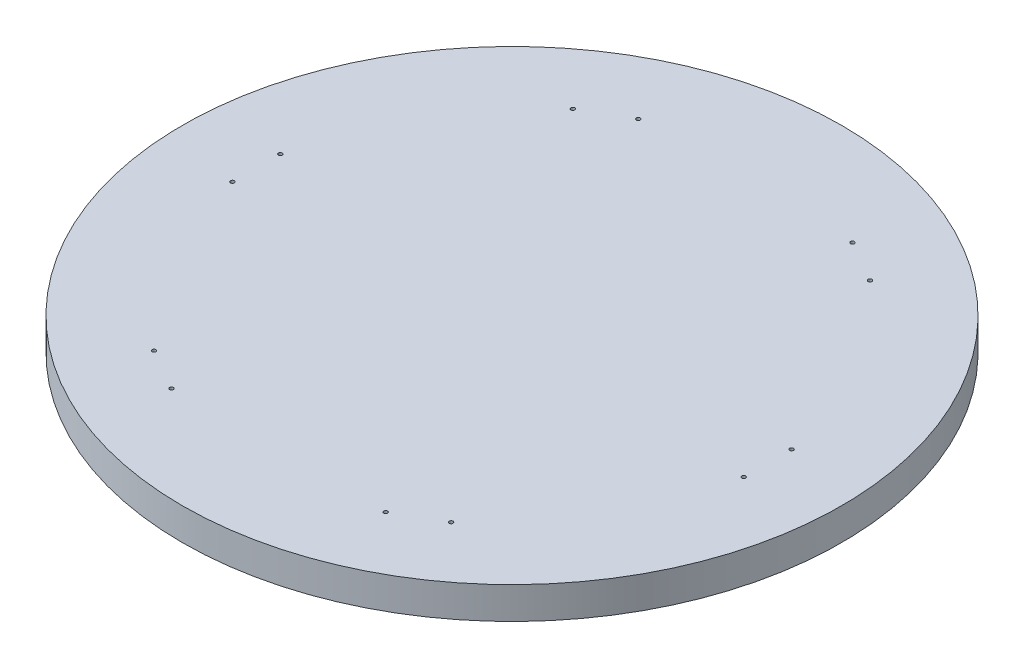
SolidWorks part; units mm, degrees
ref_plane "Front Plane" through (0, 0, 0) normal (0, 0, 1) x (1, 0, 0)
ref_plane "Top Plane" through (0, 0, 0) normal (0, 1, 0) x (1, 0, 0)
ref_plane "Right Plane" through (0, 0, 0) normal (1, 0, 0) x (0, 0, -1)
sketch "Sketch1" plane through (0, 0, 0) normal (0, 1, 0) x (1, 0, 0)
  circle A0 centre (0, 0) radius 261.9375
extrude "Boss-Extrude1" add sketch "Sketch1" along normal blind 25.4
sketch "Sketch6" plane through (0, 0, 0) normal (0, -1, 0) x (1, 0, 0)
  line L0 (203.2, 19.05) -> (203.2, -19.05) construction
  line L1 (215.9, 19.05) -> (215.9, -19.05)
  line L2 (190.5, 19.05) -> (190.5, -19.05)
  line L3 (203.2, -16.5451) -> (201.0307, -17.7976) construction
  line L4 (201.0307, -17.7976) -> (201.0307, -20.3024) construction
  line L5 (201.0307, -20.3024) -> (203.2, -21.5549) construction
  line L6 (203.2, -21.5549) -> (205.3693, -20.3024) construction
  line L7 (205.3693, -20.3024) -> (205.3693, -17.7976) construction
  line L8 (205.3693, -17.7976) -> (203.2, -16.5451) construction
  line L9 (203.2, 22.1294) -> (201.0307, 20.8769) construction
  line L10 (201.0307, 20.8769) -> (201.0307, 18.372) construction
  line L11 (201.0307, 18.372) -> (203.2, 17.1196) construction
  line L12 (203.2, 17.1196) -> (205.3693, 18.372) construction
  line L13 (205.3693, 18.372) -> (205.3693, 20.8769) construction
  line L14 (205.3693, 20.8769) -> (203.2, 22.1294) construction
  line L15 (0, 0) -> (203.2, 0) construction
  line L16 (87.2715, -184.2489) -> (85.1022, -182.9965) construction
  line L17 (85.1022, -182.9965) -> (82.9329, -184.2489) construction
  line L18 (82.9329, -184.2489) -> (82.9329, -186.7538) construction
  line L19 (82.9329, -186.7538) -> (85.1022, -188.0063) construction
  line L20 (85.1022, -188.0063) -> (87.2715, -186.7538) construction
  line L21 (87.2715, -186.7538) -> (87.2715, -184.2489) construction
  line L22 (120.7646, -164.9117) -> (118.5953, -163.6592) construction
  line L23 (118.5953, -163.6592) -> (116.426, -164.9117) construction
  line L24 (116.426, -164.9117) -> (116.426, -167.4166) construction
  line L25 (116.426, -167.4166) -> (118.5953, -168.669) construction
  line L26 (118.5953, -168.669) -> (120.7646, -167.4166) construction
  line L27 (120.7646, -167.4166) -> (120.7646, -164.9117) construction
  line L28 (0, 0) -> (101.6, -175.9764) construction
  line L29 (118.0978, -166.4514) -> (85.1022, -185.5014) construction
  line L30 (124.4478, -177.4499) -> (91.4522, -196.4999)
  line L31 (111.7478, -155.4528) -> (78.7522, -174.5028)
  line L32 (-115.9285, -167.7038) -> (-115.9285, -165.1989) construction
  line L33 (-115.9285, -165.1989) -> (-118.0978, -163.9465) construction
  line L34 (-118.0978, -163.9465) -> (-120.2671, -165.1989) construction
  line L35 (-120.2671, -165.1989) -> (-120.2671, -167.7038) construction
  line L36 (-120.2671, -167.7038) -> (-118.0978, -168.9563) construction
  line L37 (-118.0978, -168.9563) -> (-115.9285, -167.7038) construction
  line L38 (-82.4354, -187.0411) -> (-82.4354, -184.5362) construction
  line L39 (-82.4354, -184.5362) -> (-84.6047, -183.2837) construction
  line L40 (-84.6047, -183.2837) -> (-86.774, -184.5362) construction
  line L41 (-86.774, -184.5362) -> (-86.774, -187.0411) construction
  line L42 (-86.774, -187.0411) -> (-84.6047, -188.2935) construction
  line L43 (-84.6047, -188.2935) -> (-82.4354, -187.0411) construction
  line L44 (0, 0) -> (-101.6, -175.9764) construction
  line L45 (-85.1022, -185.5014) -> (-118.0978, -166.4514) construction
  line L46 (-91.4522, -196.4999) -> (-124.4478, -177.4499)
  line L47 (-78.7522, -174.5028) -> (-111.7478, -155.4528)
  line L48 (-203.2, 16.5451) -> (-201.0307, 17.7976) construction
  line L49 (-201.0307, 17.7976) -> (-201.0307, 20.3024) construction
  line L50 (-201.0307, 20.3024) -> (-203.2, 21.5549) construction
  line L51 (-203.2, 21.5549) -> (-205.3693, 20.3024) construction
  line L52 (-205.3693, 20.3024) -> (-205.3693, 17.7976) construction
  line L53 (-205.3693, 17.7976) -> (-203.2, 16.5451) construction
  line L54 (-203.2, -22.1294) -> (-201.0307, -20.8769) construction
  line L55 (-201.0307, -20.8769) -> (-201.0307, -18.372) construction
  line L56 (-201.0307, -18.372) -> (-203.2, -17.1196) construction
  line L57 (-203.2, -17.1196) -> (-205.3693, -18.372) construction
  line L58 (-205.3693, -18.372) -> (-205.3693, -20.8769) construction
  line L59 (-205.3693, -20.8769) -> (-203.2, -22.1294) construction
  line L60 (0, 0) -> (-203.2, 0) construction
  line L61 (-203.2, -19.05) -> (-203.2, 19.05) construction
  line L62 (-215.9, -19.05) -> (-215.9, 19.05)
  line L63 (-190.5, -19.05) -> (-190.5, 19.05)
  line L64 (-87.2715, 184.2489) -> (-85.1022, 182.9965) construction
  line L65 (-85.1022, 182.9965) -> (-82.9329, 184.2489) construction
  line L66 (-82.9329, 184.2489) -> (-82.9329, 186.7538) construction
  line L67 (-82.9329, 186.7538) -> (-85.1022, 188.0063) construction
  line L68 (-85.1022, 188.0063) -> (-87.2715, 186.7538) construction
  line L69 (-87.2715, 186.7538) -> (-87.2715, 184.2489) construction
  line L70 (-120.7646, 164.9117) -> (-118.5953, 163.6592) construction
  line L71 (-118.5953, 163.6592) -> (-116.426, 164.9117) construction
  line L72 (-116.426, 164.9117) -> (-116.426, 167.4166) construction
  line L73 (-116.426, 167.4166) -> (-118.5953, 168.669) construction
  line L74 (-118.5953, 168.669) -> (-120.7646, 167.4166) construction
  line L75 (-120.7646, 167.4166) -> (-120.7646, 164.9117) construction
  line L76 (0, 0) -> (-101.6, 175.9764) construction
  line L77 (-118.0978, 166.4514) -> (-85.1022, 185.5014) construction
  line L78 (-124.4478, 177.4499) -> (-91.4522, 196.4999)
  line L79 (-111.7478, 155.4528) -> (-78.7522, 174.5028)
  line L80 (115.9285, 167.7038) -> (115.9285, 165.1989) construction
  line L81 (115.9285, 165.1989) -> (118.0978, 163.9465) construction
  line L82 (118.0978, 163.9465) -> (120.2671, 165.1989) construction
  line L83 (120.2671, 165.1989) -> (120.2671, 167.7038) construction
  line L84 (120.2671, 167.7038) -> (118.0978, 168.9563) construction
  line L85 (118.0978, 168.9563) -> (115.9285, 167.7038) construction
  line L86 (82.4354, 187.0411) -> (82.4354, 184.5362) construction
  line L87 (82.4354, 184.5362) -> (84.6047, 183.2837) construction
  line L88 (84.6047, 183.2837) -> (86.774, 184.5362) construction
  line L89 (86.774, 184.5362) -> (86.774, 187.0411) construction
  line L90 (86.774, 187.0411) -> (84.6047, 188.2935) construction
  line L91 (84.6047, 188.2935) -> (82.4354, 187.0411) construction
  line L92 (0, 0) -> (101.6, 175.9764) construction
  line L93 (85.1022, 185.5014) -> (118.0978, 166.4514) construction
  line L94 (91.4522, 196.4999) -> (124.4478, 177.4499)
  line L95 (78.7522, 174.5028) -> (111.7478, 155.4528)
  arc A0 (215.9, 19.05) -> (190.5, 19.05) centre (203.2, 19.05) ccw
  arc A1 (190.5, -19.05) -> (215.9, -19.05) centre (203.2, -19.05) ccw
  circle A2 centre (203.2, -19.05) radius 2.1693 construction
  circle A3 centre (203.2, 19.6245) radius 2.1693 construction
  circle A4 centre (203.2, -19.05) radius 1.524 construction
  circle A5 centre (203.2, 19.6245) radius 1.524 construction
  circle A6 centre (85.1022, -185.5014) radius 2.1693 construction
  circle A7 centre (118.5953, -166.1641) radius 2.1693 construction
  circle A8 centre (85.1022, -185.5014) radius 1.524 construction
  circle A9 centre (118.5953, -166.1641) radius 1.524 construction
  arc A10 (124.4478, -177.4499) -> (111.7478, -155.4528) centre (118.0978, -166.4514) ccw
  arc A11 (78.7522, -174.5028) -> (91.4522, -196.4999) centre (85.1022, -185.5014) ccw
  circle A12 centre (-118.0978, -166.4514) radius 2.1693 construction
  circle A13 centre (-84.6047, -185.7886) radius 2.1693 construction
  circle A14 centre (-118.0978, -166.4514) radius 1.524 construction
  circle A15 centre (-84.6047, -185.7886) radius 1.524 construction
  arc A16 (-91.4522, -196.4999) -> (-78.7522, -174.5028) centre (-85.1022, -185.5014) ccw
  arc A17 (-111.7478, -155.4528) -> (-124.4478, -177.4499) centre (-118.0978, -166.4514) ccw
  circle A18 centre (-203.2, 19.05) radius 2.1693 construction
  circle A19 centre (-203.2, -19.6245) radius 2.1693 construction
  circle A20 centre (-203.2, 19.05) radius 1.524 construction
  circle A21 centre (-203.2, -19.6245) radius 1.524 construction
  arc A22 (-215.9, -19.05) -> (-190.5, -19.05) centre (-203.2, -19.05) ccw
  arc A23 (-190.5, 19.05) -> (-215.9, 19.05) centre (-203.2, 19.05) ccw
  circle A24 centre (-85.1022, 185.5014) radius 2.1693 construction
  circle A25 centre (-118.5953, 166.1641) radius 2.1693 construction
  circle A26 centre (-85.1022, 185.5014) radius 1.524 construction
  circle A27 centre (-118.5953, 166.1641) radius 1.524 construction
  arc A28 (-124.4478, 177.4499) -> (-111.7478, 155.4528) centre (-118.0978, 166.4514) ccw
  arc A29 (-78.7522, 174.5028) -> (-91.4522, 196.4999) centre (-85.1022, 185.5014) ccw
  circle A30 centre (118.0978, 166.4514) radius 2.1693 construction
  circle A31 centre (84.6047, 185.7886) radius 2.1693 construction
  circle A32 centre (118.0978, 166.4514) radius 1.524 construction
  circle A33 centre (84.6047, 185.7886) radius 1.524 construction
  arc A34 (91.4522, 196.4999) -> (78.7522, 174.5028) centre (85.1022, 185.5014) ccw
  arc A35 (111.7478, 155.4528) -> (124.4478, 177.4499) centre (118.0978, 166.4514) ccw
  point P2 (203.2, 0)
  point P32 (101.6, -175.9764)
  point P58 (-101.6, -175.9764)
  point P84 (-203.2, 0)
  point P110 (-101.6, 175.9764)
  point P136 (101.6, 175.9764)
  point P160 (0, 0)
  dimension "D1" = 6
extrude "Cut-Extrude4" cut sketch "Sketch6" against normal blind 12.7
sketch "Sketch9" plane through (0, 0, 0) normal (0, -1, 0) x (1, 0, 0)
  circle A0 centre (0, 0) radius 25.4
extrude "Boss-Extrude2" add sketch "Sketch9" along normal blind 10.16 and the other way through all
sketch "Sketch10" plane through (0, -10.16, 0) normal (0, -1, 0) x (1, 0, 0)
  line L0 (0, -2.032) -> (0, 1.524) construction
  line L1 (-1.344, 1.524) -> (1.344, 1.524)
  line L2 (-2.032, 0) -> (-2.032, 1.524)
  line L3 (-2.032, 1.524) -> (-1.344, 1.524)
  line L4 (2.032, 0) -> (2.032, 1.524)
  line L5 (2.032, 1.524) -> (1.344, 1.524)
  arc A0 (-2.032, 0) -> (2.032, 0) centre (0, 0) ccw
extrude "Cut-Extrude7" cut sketch "Sketch10" against normal blind 19.05
sketch "Sketch11" plane through (0, 0, 0) normal (0, -1, 0) x (1, 0, 0)
  line L0 (0, 0) -> (-11.1642, -177.4492) construction
  line L1 (0, 0) -> (0, -291.8902) construction
  line L2 (0, 0) -> (11.1642, -177.4492) construction
  line L3 (-33.3164, -174.6507) -> (-22.2403, -176.0499) construction
  line L4 (-11.1642, -177.4492) -> (0, -177.4492) construction
  line L5 (0, -177.4492) -> (11.1642, -177.4492) construction
  line L6 (-22.2403, -176.0499) -> (-11.1642, -177.4492) construction
  line L7 (-54.9432, -169.0978) -> (-44.1298, -171.8743) construction
  line L8 (-44.1298, -171.8743) -> (-33.3164, -174.6507) construction
  line L9 (-75.7036, -160.8782) -> (-65.3234, -164.988) construction
  line L10 (-65.3234, -164.988) -> (-54.9432, -169.0978) construction
  line L11 (-95.27, -150.1215) -> (-85.4868, -155.4999) construction
  line L12 (-85.4868, -155.4999) -> (-75.7036, -160.8782) construction
  line L13 (-113.334, -136.9973) -> (-104.302, -143.5594) construction
  line L14 (-104.302, -143.5594) -> (-95.27, -150.1215) construction
  line L15 (-129.6106, -121.7125) -> (-121.4723, -129.3549) construction
  line L16 (-121.4723, -129.3549) -> (-113.334, -136.9973) construction
  line L17 (-143.8432, -104.5082) -> (-136.7269, -113.1103) construction
  line L18 (-136.7269, -113.1103) -> (-129.6106, -121.7125) construction
  line L19 (-155.8073, -85.6558) -> (-149.8253, -95.082) construction
  line L20 (-149.8253, -95.082) -> (-143.8432, -104.5082) construction
  line L21 (-165.3143, -65.4525) -> (-160.5608, -75.5542) construction
  line L22 (-160.5608, -75.5542) -> (-155.8073, -85.6558) construction
  line L23 (-172.2141, -44.2171) -> (-168.7642, -54.8348) construction
  line L24 (-168.7642, -54.8348) -> (-165.3143, -65.4525) construction
  line L25 (-176.398, -22.2842) -> (-174.306, -33.2507) construction
  line L26 (-174.306, -33.2507) -> (-172.2141, -44.2171) construction
  line L27 (-177.8, 0) -> (-177.099, -11.1421) construction
  line L28 (-177.099, -11.1421) -> (-176.398, -22.2842) construction
  line L29 (-176.398, 22.2842) -> (-177.099, 11.1421) construction
  line L30 (-177.099, 11.1421) -> (-177.8, 0) construction
  line L31 (-172.2141, 44.2171) -> (-174.306, 33.2507) construction
  line L32 (-174.306, 33.2507) -> (-176.398, 22.2842) construction
  line L33 (-165.3143, 65.4525) -> (-168.7642, 54.8348) construction
  line L34 (-168.7642, 54.8348) -> (-172.2141, 44.2171) construction
  line L35 (-155.8073, 85.6558) -> (-160.5608, 75.5542) construction
  line L36 (-160.5608, 75.5542) -> (-165.3143, 65.4525) construction
  line L37 (-143.8432, 104.5082) -> (-149.8253, 95.082) construction
  line L38 (-149.8253, 95.082) -> (-155.8073, 85.6558) construction
  line L39 (-129.6106, 121.7125) -> (-136.7269, 113.1103) construction
  line L40 (-136.7269, 113.1103) -> (-143.8432, 104.5082) construction
  line L41 (-113.334, 136.9973) -> (-121.4723, 129.3549) construction
  line L42 (-121.4723, 129.3549) -> (-129.6106, 121.7125) construction
  line L43 (-95.27, 150.1215) -> (-104.302, 143.5594) construction
  line L44 (-104.302, 143.5594) -> (-113.334, 136.9973) construction
  line L45 (-75.7036, 160.8782) -> (-85.4868, 155.4999) construction
  line L46 (-85.4868, 155.4999) -> (-95.27, 150.1215) construction
  line L47 (-54.9432, 169.0978) -> (-65.3234, 164.988) construction
  line L48 (-65.3234, 164.988) -> (-75.7036, 160.8782) construction
  line L49 (-33.3164, 174.6507) -> (-44.1298, 171.8743) construction
  line L50 (-44.1298, 171.8743) -> (-54.9432, 169.0978) construction
  line L51 (-11.1642, 177.4492) -> (-22.2403, 176.0499) construction
  line L52 (-22.2403, 176.0499) -> (-33.3164, 174.6507) construction
  line L53 (11.1642, 177.4492) -> (0, 177.4492) construction
  line L54 (0, 177.4492) -> (-11.1642, 177.4492) construction
  line L55 (33.3164, 174.6507) -> (22.2403, 176.0499) construction
  line L56 (22.2403, 176.0499) -> (11.1642, 177.4492) construction
  line L57 (54.9432, 169.0978) -> (44.1298, 171.8743) construction
  line L58 (44.1298, 171.8743) -> (33.3164, 174.6507) construction
  line L59 (75.7036, 160.8782) -> (65.3234, 164.988) construction
  line L60 (65.3234, 164.988) -> (54.9432, 169.0978) construction
  line L61 (95.27, 150.1215) -> (85.4868, 155.4999) construction
  line L62 (85.4868, 155.4999) -> (75.7036, 160.8782) construction
  line L63 (113.334, 136.9973) -> (104.302, 143.5594) construction
  line L64 (104.302, 143.5594) -> (95.27, 150.1215) construction
  line L65 (129.6106, 121.7125) -> (121.4723, 129.3549) construction
  line L66 (121.4723, 129.3549) -> (113.334, 136.9973) construction
  line L67 (143.8432, 104.5082) -> (136.7269, 113.1103) construction
  line L68 (136.7269, 113.1103) -> (129.6106, 121.7125) construction
  line L69 (155.8073, 85.6558) -> (149.8253, 95.082) construction
  line L70 (149.8253, 95.082) -> (143.8432, 104.5082) construction
  line L71 (165.3143, 65.4525) -> (160.5608, 75.5542) construction
  line L72 (160.5608, 75.5542) -> (155.8073, 85.6558) construction
  line L73 (172.2141, 44.2171) -> (168.7642, 54.8348) construction
  line L74 (168.7642, 54.8348) -> (165.3143, 65.4525) construction
  line L75 (176.398, 22.2842) -> (174.306, 33.2507) construction
  line L76 (174.306, 33.2507) -> (172.2141, 44.2171) construction
  line L77 (177.8, 0) -> (177.099, 11.1421) construction
  line L78 (177.099, 11.1421) -> (176.398, 22.2842) construction
  line L79 (176.398, -22.2842) -> (177.099, -11.1421) construction
  line L80 (177.099, -11.1421) -> (177.8, 0) construction
  line L81 (172.2141, -44.2171) -> (174.306, -33.2507) construction
  line L82 (174.306, -33.2507) -> (176.398, -22.2842) construction
  line L83 (165.3143, -65.4525) -> (168.7642, -54.8348) construction
  line L84 (168.7642, -54.8348) -> (172.2141, -44.2171) construction
  line L85 (155.8073, -85.6558) -> (160.5608, -75.5542) construction
  line L86 (160.5608, -75.5542) -> (165.3143, -65.4525) construction
  line L87 (143.8432, -104.5082) -> (149.8253, -95.082) construction
  line L88 (149.8253, -95.082) -> (155.8073, -85.6558) construction
  line L89 (129.6106, -121.7125) -> (136.7269, -113.1103) construction
  line L90 (136.7269, -113.1103) -> (143.8432, -104.5082) construction
  line L91 (113.334, -136.9973) -> (121.4723, -129.3549) construction
  line L92 (121.4723, -129.3549) -> (129.6106, -121.7125) construction
  line L93 (95.27, -150.1215) -> (104.302, -143.5594) construction
  line L94 (104.302, -143.5594) -> (113.334, -136.9973) construction
  line L95 (75.7036, -160.8782) -> (85.4868, -155.4999) construction
  line L96 (85.4868, -155.4999) -> (95.27, -150.1215) construction
  line L97 (54.9432, -169.0978) -> (65.3234, -164.988) construction
  line L98 (65.3234, -164.988) -> (75.7036, -160.8782) construction
  line L99 (33.3164, -174.6507) -> (44.1298, -171.8743) construction
  line L100 (44.1298, -171.8743) -> (54.9432, -169.0978) construction
  line L101 (11.1642, -177.4492) -> (22.2403, -176.0499) construction
  line L102 (22.2403, -176.0499) -> (33.3164, -174.6507) construction
  circle A0 centre (0, 0) radius 177.8 construction
  arc A1 (0, -177.4492) -> (-11.1201, -176.7495) centre (-5.5821, -177.4492) ccw
  arc A2 (0, -177.4492) -> (11.1201, -176.7495) centre (5.5821, -177.4492) ccw
  arc A3 (-22.2403, -176.0499) -> (-33.185, -173.9621) centre (-27.7783, -175.3503) ccw
  arc A4 (-22.2403, -176.0499) -> (-11.1201, -176.7495) centre (-16.7022, -176.7495) ccw
  arc A5 (-44.1298, -171.8743) -> (-54.7266, -168.4312) centre (-49.5365, -170.4861) ccw
  arc A6 (-44.1298, -171.8743) -> (-33.185, -173.9621) centre (-38.7231, -173.2625) ccw
  arc A7 (-65.3234, -164.988) -> (-75.4051, -160.244) centre (-70.5135, -162.9331) ccw
  arc A8 (-65.3234, -164.988) -> (-54.7266, -168.4312) centre (-60.1333, -167.0429) ccw
  arc A9 (-85.4868, -155.4999) -> (-94.8944, -149.5296) centre (-90.3784, -152.8107) ccw
  arc A10 (-85.4868, -155.4999) -> (-75.4051, -160.244) centre (-80.5952, -158.1891) ccw
  arc A11 (-104.302, -143.5594) -> (-112.8871, -136.4571) centre (-108.818, -140.2783) ccw
  arc A12 (-104.302, -143.5594) -> (-94.8944, -149.5296) centre (-99.786, -146.8404) ccw
  arc A13 (-121.4723, -129.3549) -> (-129.0996, -121.2326) centre (-125.5415, -125.5337) ccw
  arc A14 (-121.4723, -129.3549) -> (-112.8871, -136.4571) centre (-117.4031, -133.1761) ccw
  arc A15 (-136.7269, -113.1103) -> (-143.2761, -104.0962) centre (-140.2851, -108.8093) ccw
  arc A16 (-136.7269, -113.1103) -> (-129.0996, -121.2326) centre (-133.1688, -117.4114) ccw
  arc A17 (-149.8253, -95.082) -> (-155.193, -85.3181) centre (-152.8163, -90.3689) ccw
  arc A18 (-149.8253, -95.082) -> (-143.2761, -104.0962) centre (-146.8342, -99.7951) ccw
  arc A19 (-160.5608, -75.5542) -> (-164.6625, -65.1945) centre (-162.9375, -70.5034) ccw
  arc A20 (-160.5608, -75.5542) -> (-155.193, -85.3181) centre (-158.1841, -80.605) ccw
  arc A21 (-168.7642, -54.8348) -> (-171.5351, -44.0427) centre (-170.4891, -49.5259) ccw
  arc A22 (-168.7642, -54.8348) -> (-164.6625, -65.1945) centre (-167.0392, -60.1437) ccw
  arc A23 (-174.306, -33.2507) -> (-175.7025, -22.1964) centre (-175.352, -27.7675) ccw
  arc A24 (-174.306, -33.2507) -> (-171.5351, -44.0427) centre (-173.2601, -38.7339) ccw
  arc A25 (-177.099, -11.1421) -> (-177.099, 0) centre (-177.4495, -5.5711) ccw
  arc A26 (-177.099, -11.1421) -> (-175.7025, -22.1964) centre (-176.7485, -16.7132) ccw
  arc A27 (-177.099, 11.1421) -> (-175.7025, 22.1964) centre (-176.7485, 16.7132) ccw
  arc A28 (-177.099, 11.1421) -> (-177.099, 0) centre (-177.4495, 5.5711) ccw
  arc A29 (-174.306, 33.2507) -> (-171.5351, 44.0427) centre (-173.2601, 38.7339) ccw
  arc A30 (-174.306, 33.2507) -> (-175.7025, 22.1964) centre (-175.352, 27.7675) ccw
  arc A31 (-168.7642, 54.8348) -> (-164.6625, 65.1945) centre (-167.0392, 60.1437) ccw
  arc A32 (-168.7642, 54.8348) -> (-171.5351, 44.0427) centre (-170.4891, 49.5259) ccw
  arc A33 (-160.5608, 75.5542) -> (-155.193, 85.3181) centre (-158.1841, 80.605) ccw
  arc A34 (-160.5608, 75.5542) -> (-164.6625, 65.1945) centre (-162.9375, 70.5034) ccw
  arc A35 (-149.8253, 95.082) -> (-143.2761, 104.0962) centre (-146.8342, 99.7951) ccw
  arc A36 (-149.8253, 95.082) -> (-155.193, 85.3181) centre (-152.8163, 90.3689) ccw
  arc A37 (-136.7269, 113.1103) -> (-129.0996, 121.2326) centre (-133.1688, 117.4114) ccw
  arc A38 (-136.7269, 113.1103) -> (-143.2761, 104.0962) centre (-140.2851, 108.8093) ccw
  arc A39 (-121.4723, 129.3549) -> (-112.8871, 136.4571) centre (-117.4031, 133.1761) ccw
  arc A40 (-121.4723, 129.3549) -> (-129.0996, 121.2326) centre (-125.5415, 125.5337) ccw
  arc A41 (-104.302, 143.5594) -> (-94.8944, 149.5296) centre (-99.786, 146.8404) ccw
  arc A42 (-104.302, 143.5594) -> (-112.8871, 136.4571) centre (-108.818, 140.2783) ccw
  arc A43 (-85.4868, 155.4999) -> (-75.4051, 160.244) centre (-80.5952, 158.1891) ccw
  arc A44 (-85.4868, 155.4999) -> (-94.8944, 149.5296) centre (-90.3784, 152.8107) ccw
  arc A45 (-65.3234, 164.988) -> (-54.7266, 168.4312) centre (-60.1333, 167.0429) ccw
  arc A46 (-65.3234, 164.988) -> (-75.4051, 160.244) centre (-70.5135, 162.9331) ccw
  arc A47 (-44.1298, 171.8743) -> (-33.185, 173.9621) centre (-38.7231, 173.2625) ccw
  arc A48 (-44.1298, 171.8743) -> (-54.7266, 168.4312) centre (-49.5365, 170.4861) ccw
  arc A49 (-22.2403, 176.0499) -> (-11.1201, 176.7495) centre (-16.7022, 176.7495) ccw
  arc A50 (-22.2403, 176.0499) -> (-33.185, 173.9621) centre (-27.7783, 175.3503) ccw
  arc A51 (0, 177.4492) -> (11.1201, 176.7495) centre (5.5821, 177.4492) ccw
  arc A52 (0, 177.4492) -> (-11.1201, 176.7495) centre (-5.5821, 177.4492) ccw
  arc A53 (22.2403, 176.0499) -> (33.185, 173.9621) centre (27.7783, 175.3503) ccw
  arc A54 (22.2403, 176.0499) -> (11.1201, 176.7495) centre (16.7022, 176.7495) ccw
  arc A55 (44.1298, 171.8743) -> (54.7266, 168.4312) centre (49.5365, 170.4861) ccw
  arc A56 (44.1298, 171.8743) -> (33.185, 173.9621) centre (38.7231, 173.2625) ccw
  arc A57 (65.3234, 164.988) -> (75.4051, 160.244) centre (70.5135, 162.9331) ccw
  arc A58 (65.3234, 164.988) -> (54.7266, 168.4312) centre (60.1333, 167.0429) ccw
  arc A59 (85.4868, 155.4999) -> (94.8944, 149.5296) centre (90.3784, 152.8107) ccw
  arc A60 (85.4868, 155.4999) -> (75.4051, 160.244) centre (80.5952, 158.1891) ccw
  arc A61 (104.302, 143.5594) -> (112.8871, 136.4571) centre (108.818, 140.2783) ccw
  arc A62 (104.302, 143.5594) -> (94.8944, 149.5296) centre (99.786, 146.8404) ccw
  arc A63 (121.4723, 129.3549) -> (129.0996, 121.2326) centre (125.5415, 125.5337) ccw
  arc A64 (121.4723, 129.3549) -> (112.8871, 136.4571) centre (117.4031, 133.1761) ccw
  arc A65 (136.7269, 113.1103) -> (143.2761, 104.0962) centre (140.2851, 108.8093) ccw
  arc A66 (136.7269, 113.1103) -> (129.0996, 121.2326) centre (133.1688, 117.4114) ccw
  arc A67 (149.8253, 95.082) -> (155.193, 85.3181) centre (152.8163, 90.3689) ccw
  arc A68 (149.8253, 95.082) -> (143.2761, 104.0962) centre (146.8342, 99.7951) ccw
  arc A69 (160.5608, 75.5542) -> (164.6625, 65.1945) centre (162.9375, 70.5034) ccw
  arc A70 (160.5608, 75.5542) -> (155.193, 85.3181) centre (158.1841, 80.605) ccw
  arc A71 (168.7642, 54.8348) -> (171.5351, 44.0427) centre (170.4891, 49.5259) ccw
  arc A72 (168.7642, 54.8348) -> (164.6625, 65.1945) centre (167.0392, 60.1437) ccw
  arc A73 (174.306, 33.2507) -> (175.7025, 22.1964) centre (175.352, 27.7675) ccw
  arc A74 (174.306, 33.2507) -> (171.5351, 44.0427) centre (173.2601, 38.7339) ccw
  arc A75 (177.099, 11.1421) -> (177.099, 0) centre (177.4495, 5.5711) ccw
  arc A76 (177.099, 11.1421) -> (175.7025, 22.1964) centre (176.7485, 16.7132) ccw
  arc A77 (177.099, -11.1421) -> (175.7025, -22.1964) centre (176.7485, -16.7132) ccw
  arc A78 (177.099, -11.1421) -> (177.099, 0) centre (177.4495, -5.5711) ccw
  arc A79 (174.306, -33.2507) -> (171.5351, -44.0427) centre (173.2601, -38.7339) ccw
  arc A80 (174.306, -33.2507) -> (175.7025, -22.1964) centre (175.352, -27.7675) ccw
  arc A81 (168.7642, -54.8348) -> (164.6625, -65.1945) centre (167.0392, -60.1437) ccw
  arc A82 (168.7642, -54.8348) -> (171.5351, -44.0427) centre (170.4891, -49.5259) ccw
  arc A83 (160.5608, -75.5542) -> (155.193, -85.3181) centre (158.1841, -80.605) ccw
  arc A84 (160.5608, -75.5542) -> (164.6625, -65.1945) centre (162.9375, -70.5034) ccw
  arc A85 (149.8253, -95.082) -> (143.2761, -104.0962) centre (146.8342, -99.7951) ccw
  arc A86 (149.8253, -95.082) -> (155.193, -85.3181) centre (152.8163, -90.3689) ccw
  arc A87 (136.7269, -113.1103) -> (129.0996, -121.2326) centre (133.1688, -117.4114) ccw
  arc A88 (136.7269, -113.1103) -> (143.2761, -104.0962) centre (140.2851, -108.8093) ccw
  arc A89 (121.4723, -129.3549) -> (112.8871, -136.4571) centre (117.4031, -133.1761) ccw
  arc A90 (121.4723, -129.3549) -> (129.0996, -121.2326) centre (125.5415, -125.5337) ccw
  arc A91 (104.302, -143.5594) -> (94.8944, -149.5296) centre (99.786, -146.8404) ccw
  arc A92 (104.302, -143.5594) -> (112.8871, -136.4571) centre (108.818, -140.2783) ccw
  arc A93 (85.4868, -155.4999) -> (75.4051, -160.244) centre (80.5952, -158.1891) ccw
  arc A94 (85.4868, -155.4999) -> (94.8944, -149.5296) centre (90.3784, -152.8107) ccw
  arc A95 (65.3234, -164.988) -> (54.7266, -168.4312) centre (60.1333, -167.0429) ccw
  arc A96 (65.3234, -164.988) -> (75.4051, -160.244) centre (70.5135, -162.9331) ccw
  arc A97 (44.1298, -171.8743) -> (33.185, -173.9621) centre (38.7231, -173.2625) ccw
  arc A98 (44.1298, -171.8743) -> (54.7266, -168.4312) centre (49.5365, -170.4861) ccw
  arc A99 (22.2403, -176.0499) -> (11.1201, -176.7495) centre (16.7022, -176.7495) ccw
  arc A100 (22.2403, -176.0499) -> (33.185, -173.9621) centre (27.7783, -175.3503) ccw
  circle A101 centre (0, 0) radius 27.7675
  point P356 (0, 0)
  dimension "D1" = 50
extrude "Cut-Extrude9" cut sketch "Sketch11" against normal blind 6.35
sketch "Sketch12" plane through (0, 12.7, 0) normal (0, -1, 0) x (1, 0, 0)
  line L0 (203.2, 19.05) -> (203.2, -19.05) construction
  line L1 (215.9, 19.05) -> (215.9, -19.05) construction
  line L2 (190.5, 19.05) -> (190.5, -19.05) construction
  line L3 (203.2, -16.5451) -> (201.0307, -17.7975) construction
  line L4 (201.0307, -17.7975) -> (201.0307, -20.3024) construction
  line L5 (201.0307, -20.3024) -> (203.2, -21.5549) construction
  line L6 (203.2, -21.5549) -> (205.3693, -20.3024) construction
  line L7 (205.3693, -20.3024) -> (205.3693, -17.7975) construction
  line L8 (205.3693, -17.7975) -> (203.2, -16.5451) construction
  line L9 (203.2, 21.5549) -> (201.0307, 20.3025) construction
  line L10 (201.0307, 20.3025) -> (201.0307, 17.7976) construction
  line L11 (201.0307, 17.7976) -> (203.2, 16.5451) construction
  line L12 (203.2, 16.5451) -> (205.3693, 17.7976) construction
  line L13 (205.3693, 17.7976) -> (205.3693, 20.3025) construction
  line L14 (205.3693, 20.3025) -> (203.2, 21.5549) construction
  line L15 (190.5, -19.05) -> (203.2, -19.05) construction
  line L16 (87.2715, -184.2489) -> (85.1022, -182.9965) construction
  line L17 (85.1022, -182.9965) -> (82.9329, -184.2489) construction
  line L18 (82.9329, -184.2489) -> (82.9329, -186.7538) construction
  line L19 (82.9329, -186.7538) -> (85.1022, -188.0062) construction
  line L20 (85.1022, -188.0062) -> (87.2715, -186.7538) construction
  line L21 (87.2715, -186.7538) -> (87.2715, -184.2489) construction
  line L22 (120.2671, -165.1989) -> (118.0978, -163.9465) construction
  line L23 (118.0978, -163.9465) -> (115.9285, -165.1989) construction
  line L24 (115.9285, -165.1989) -> (115.9285, -167.7038) construction
  line L25 (115.9285, -167.7038) -> (118.0978, -168.9562) construction
  line L26 (118.0978, -168.9562) -> (120.2671, -167.7038) construction
  line L27 (120.2671, -167.7038) -> (120.2671, -165.1989) construction
  line L28 (78.7522, -174.5028) -> (85.1022, -185.5014) construction
  line L29 (118.0978, -166.4514) -> (85.1022, -185.5014) construction
  line L30 (124.4478, -177.4499) -> (91.4522, -196.4999) construction
  line L31 (111.7478, -155.4528) -> (78.7522, -174.5028) construction
  line L32 (-115.9285, -167.7038) -> (-115.9285, -165.1989) construction
  line L33 (-115.9285, -165.1989) -> (-118.0978, -163.9465) construction
  line L34 (-118.0978, -163.9465) -> (-120.2671, -165.1989) construction
  line L35 (-120.2671, -165.1989) -> (-120.2671, -167.7038) construction
  line L36 (-120.2671, -167.7038) -> (-118.0978, -168.9563) construction
  line L37 (-118.0978, -168.9563) -> (-115.9285, -167.7038) construction
  line L38 (-82.9329, -186.7538) -> (-82.9329, -184.2489) construction
  line L39 (-82.9329, -184.2489) -> (-85.1022, -182.9965) construction
  line L40 (-85.1022, -182.9965) -> (-87.2715, -184.2489) construction
  line L41 (-87.2715, -184.2489) -> (-87.2715, -186.7538) construction
  line L42 (-87.2715, -186.7538) -> (-85.1022, -188.0063) construction
  line L43 (-85.1022, -188.0063) -> (-82.9329, -186.7538) construction
  line L44 (-111.7478, -155.4528) -> (-118.0978, -166.4514) construction
  line L45 (-85.1022, -185.5014) -> (-118.0978, -166.4514) construction
  line L46 (-91.4522, -196.4999) -> (-124.4478, -177.4499) construction
  line L47 (-78.7522, -174.5028) -> (-111.7478, -155.4528) construction
  line L48 (-203.2, 16.5451) -> (-201.0307, 17.7975) construction
  line L49 (-201.0307, 17.7975) -> (-201.0307, 20.3024) construction
  line L50 (-201.0307, 20.3024) -> (-203.2, 21.5549) construction
  line L51 (-203.2, 21.5549) -> (-205.3693, 20.3024) construction
  line L52 (-205.3693, 20.3024) -> (-205.3693, 17.7975) construction
  line L53 (-205.3693, 17.7975) -> (-203.2, 16.5451) construction
  line L54 (-203.2, -21.5549) -> (-201.0307, -20.3025) construction
  line L55 (-201.0307, -20.3025) -> (-201.0307, -17.7976) construction
  line L56 (-201.0307, -17.7976) -> (-203.2, -16.5451) construction
  line L57 (-203.2, -16.5451) -> (-205.3693, -17.7976) construction
  line L58 (-205.3693, -17.7976) -> (-205.3693, -20.3025) construction
  line L59 (-205.3693, -20.3025) -> (-203.2, -21.5549) construction
  line L60 (-190.5, 19.05) -> (-203.2, 19.05) construction
  line L61 (-203.2, -19.05) -> (-203.2, 19.05) construction
  line L62 (-215.9, -19.05) -> (-215.9, 19.05) construction
  line L63 (-190.5, -19.05) -> (-190.5, 19.05) construction
  line L64 (-87.2715, 184.2489) -> (-85.1022, 182.9965) construction
  line L65 (-85.1022, 182.9965) -> (-82.9329, 184.2489) construction
  line L66 (-82.9329, 184.2489) -> (-82.9329, 186.7538) construction
  line L67 (-82.9329, 186.7538) -> (-85.1022, 188.0062) construction
  line L68 (-85.1022, 188.0062) -> (-87.2715, 186.7538) construction
  line L69 (-87.2715, 186.7538) -> (-87.2715, 184.2489) construction
  line L70 (-120.2671, 165.1989) -> (-118.0978, 163.9465) construction
  line L71 (-118.0978, 163.9465) -> (-115.9285, 165.1989) construction
  line L72 (-115.9285, 165.1989) -> (-115.9285, 167.7038) construction
  line L73 (-115.9285, 167.7038) -> (-118.0978, 168.9562) construction
  line L74 (-118.0978, 168.9562) -> (-120.2671, 167.7038) construction
  line L75 (-120.2671, 167.7038) -> (-120.2671, 165.1989) construction
  line L76 (-78.7522, 174.5028) -> (-85.1022, 185.5014) construction
  line L77 (-118.0978, 166.4514) -> (-85.1022, 185.5014) construction
  line L78 (-124.4478, 177.4499) -> (-91.4522, 196.4999) construction
  line L79 (-111.7478, 155.4528) -> (-78.7522, 174.5028) construction
  line L80 (115.9285, 167.7038) -> (115.9285, 165.1989) construction
  line L81 (115.9285, 165.1989) -> (118.0978, 163.9465) construction
  line L82 (118.0978, 163.9465) -> (120.2671, 165.1989) construction
  line L83 (120.2671, 165.1989) -> (120.2671, 167.7038) construction
  line L84 (120.2671, 167.7038) -> (118.0978, 168.9563) construction
  line L85 (118.0978, 168.9563) -> (115.9285, 167.7038) construction
  line L86 (82.9329, 186.7538) -> (82.9329, 184.2489) construction
  line L87 (82.9329, 184.2489) -> (85.1022, 182.9965) construction
  line L88 (85.1022, 182.9965) -> (87.2715, 184.2489) construction
  line L89 (87.2715, 184.2489) -> (87.2715, 186.7538) construction
  line L90 (87.2715, 186.7538) -> (85.1022, 188.0063) construction
  line L91 (85.1022, 188.0063) -> (82.9329, 186.7538) construction
  line L92 (111.7478, 155.4528) -> (118.0978, 166.4514) construction
  line L93 (85.1022, 185.5014) -> (118.0978, 166.4514) construction
  line L94 (91.4522, 196.4999) -> (124.4478, 177.4499) construction
  line L95 (78.7522, 174.5028) -> (111.7478, 155.4528) construction
  line L96 (0, 0) -> (-101.6, 175.9764) construction
  arc A0 (215.9, 19.05) -> (190.5, 19.05) centre (203.2, 19.05) ccw construction
  arc A1 (190.5, -19.05) -> (215.9, -19.05) centre (203.2, -19.05) ccw construction
  circle A2 centre (203.2, -19.05) radius 2.1693 construction
  circle A3 centre (203.2, 19.05) radius 2.1693 construction
  circle A4 centre (203.2, -19.05) radius 1.524
  circle A5 centre (203.2, 19.05) radius 1.524
  circle A6 centre (85.1022, -185.5014) radius 1.524
  circle A7 centre (118.0978, -166.4514) radius 1.524
  circle A8 centre (85.1022, -185.5014) radius 2.1693 construction
  circle A9 centre (118.0978, -166.4514) radius 2.1693 construction
  arc A10 (124.4478, -177.4499) -> (111.7478, -155.4528) centre (118.0978, -166.4514) ccw construction
  arc A11 (78.7522, -174.5028) -> (91.4522, -196.4999) centre (85.1022, -185.5014) ccw construction
  circle A12 centre (-118.0978, -166.4514) radius 1.524
  circle A13 centre (-85.1022, -185.5014) radius 1.524
  circle A14 centre (-118.0978, -166.4514) radius 2.1693 construction
  circle A15 centre (-85.1022, -185.5014) radius 2.1693 construction
  arc A16 (-91.4522, -196.4999) -> (-78.7522, -174.5028) centre (-85.1022, -185.5014) ccw construction
  arc A17 (-111.7478, -155.4528) -> (-124.4478, -177.4499) centre (-118.0978, -166.4514) ccw construction
  circle A18 centre (-203.2, 19.05) radius 1.524
  circle A19 centre (-203.2, -19.05) radius 1.524
  circle A20 centre (-203.2, 19.05) radius 2.1693 construction
  circle A21 centre (-203.2, -19.05) radius 2.1693 construction
  arc A22 (-215.9, -19.05) -> (-190.5, -19.05) centre (-203.2, -19.05) ccw construction
  arc A23 (-190.5, 19.05) -> (-215.9, 19.05) centre (-203.2, 19.05) ccw construction
  circle A24 centre (-85.1022, 185.5014) radius 1.524
  circle A25 centre (-118.0978, 166.4514) radius 1.524
  circle A26 centre (-85.1022, 185.5014) radius 2.1693 construction
  circle A27 centre (-118.0978, 166.4514) radius 2.1693 construction
  arc A28 (-124.4478, 177.4499) -> (-111.7478, 155.4528) centre (-118.0978, 166.4514) ccw construction
  arc A29 (-78.7522, 174.5028) -> (-91.4522, 196.4999) centre (-85.1022, 185.5014) ccw construction
  circle A30 centre (118.0978, 166.4514) radius 1.524
  circle A31 centre (85.1022, 185.5014) radius 1.524
  circle A32 centre (118.0978, 166.4514) radius 2.1693 construction
  circle A33 centre (85.1022, 185.5014) radius 2.1693 construction
  arc A34 (91.4522, 196.4999) -> (78.7522, 174.5028) centre (85.1022, 185.5014) ccw construction
  arc A35 (111.7478, 155.4528) -> (124.4478, 177.4499) centre (118.0978, 166.4514) ccw construction
  point P2 (203.2, 0)
  point P29 (101.6, -175.9764)
  point P56 (-101.6, -175.9764)
  point P83 (-203.2, 0)
  point P110 (-101.6, 175.9764)
  point P137 (101.6, 175.9764)
  point P162 (0, 0)
extrude "Cut-Extrude10" cut sketch "Sketch12" against normal through all
sketch "Sketch13" plane through (0, 0, 0) normal (0, -1, 0) x (1, 0, 0)
  line L3 (-33.3164, -174.6507) -> (-22.2403, -176.0499) construction
  line L4 (-11.1642, -177.4492) -> (0, -177.4492) construction
  line L5 (0, -177.4492) -> (11.1642, -177.4492) construction
  line L6 (-22.2403, -176.0499) -> (-11.1642, -177.4492) construction
  line L7 (-54.9432, -169.0978) -> (-44.1298, -171.8743) construction
  line L8 (-44.1298, -171.8743) -> (-33.3164, -174.6507) construction
  line L9 (-75.7036, -160.8782) -> (-65.3234, -164.988) construction
  line L10 (-65.3234, -164.988) -> (-54.9432, -169.0978) construction
  line L11 (-95.27, -150.1215) -> (-85.4868, -155.4999) construction
  line L12 (-85.4868, -155.4999) -> (-75.7036, -160.8782) construction
  line L13 (-113.334, -136.9973) -> (-104.302, -143.5594) construction
  line L14 (-104.302, -143.5594) -> (-95.27, -150.1215) construction
  line L15 (-129.6106, -121.7125) -> (-121.4723, -129.3549) construction
  line L16 (-121.4723, -129.3549) -> (-113.334, -136.9973) construction
  line L17 (-143.8432, -104.5082) -> (-136.7269, -113.1103) construction
  line L18 (-136.7269, -113.1103) -> (-129.6106, -121.7125) construction
  line L19 (-155.8073, -85.6558) -> (-149.8253, -95.082) construction
  line L20 (-149.8253, -95.082) -> (-143.8432, -104.5082) construction
  line L21 (-165.3143, -65.4525) -> (-160.5608, -75.5542) construction
  line L22 (-160.5608, -75.5542) -> (-155.8073, -85.6558) construction
  line L23 (-172.2141, -44.2171) -> (-168.7642, -54.8348) construction
  line L24 (-168.7642, -54.8348) -> (-165.3143, -65.4525) construction
  line L25 (-176.398, -22.2842) -> (-174.306, -33.2507) construction
  line L26 (-174.306, -33.2507) -> (-172.2141, -44.2171) construction
  line L45 (-75.7036, 160.8782) -> (-85.4868, 155.4999) construction
  line L46 (-85.4868, 155.4999) -> (-95.27, 150.1215) construction
  line L47 (-54.9432, 169.0978) -> (-65.3234, 164.988) construction
  line L48 (-65.3234, 164.988) -> (-75.7036, 160.8782) construction
  line L49 (-33.3164, 174.6507) -> (-44.1298, 171.8743) construction
  line L50 (-44.1298, 171.8743) -> (-54.9432, 169.0978) construction
  line L51 (-11.1642, 177.4492) -> (-22.2403, 176.0499) construction
  line L52 (-22.2403, 176.0499) -> (-33.3164, 174.6507) construction
  line L53 (11.1642, 177.4492) -> (0, 177.4492) construction
  line L54 (0, 177.4492) -> (-11.1642, 177.4492) construction
  line L55 (33.3164, 174.6507) -> (22.2403, 176.0499) construction
  line L56 (22.2403, 176.0499) -> (11.1642, 177.4492) construction
  line L57 (54.9432, 169.0978) -> (44.1298, 171.8743) construction
  line L58 (44.1298, 171.8743) -> (33.3164, 174.6507) construction
  line L59 (75.7036, 160.8782) -> (65.3234, 164.988) construction
  line L60 (65.3234, 164.988) -> (54.9432, 169.0978) construction
  line L61 (95.27, 150.1215) -> (85.4868, 155.4999) construction
  line L62 (85.4868, 155.4999) -> (75.7036, 160.8782) construction
  line L63 (113.334, 136.9973) -> (104.302, 143.5594) construction
  line L64 (104.302, 143.5594) -> (95.27, 150.1215) construction
  line L65 (129.6106, 121.7125) -> (121.4723, 129.3549) construction
  line L66 (121.4723, 129.3549) -> (113.334, 136.9973) construction
  line L67 (143.8432, 104.5082) -> (136.7269, 113.1103) construction
  line L68 (136.7269, 113.1103) -> (129.6106, 121.7125) construction
  line L69 (155.8073, 85.6558) -> (149.8253, 95.082) construction
  line L70 (149.8253, 95.082) -> (143.8432, 104.5082) construction
  line L71 (165.3143, 65.4525) -> (160.5608, 75.5542) construction
  line L72 (160.5608, 75.5542) -> (155.8073, 85.6558) construction
  line L73 (172.2141, 44.2171) -> (168.7642, 54.8348) construction
  line L74 (168.7642, 54.8348) -> (165.3143, 65.4525) construction
  line L75 (176.398, 22.2842) -> (174.306, 33.2507) construction
  line L76 (174.306, 33.2507) -> (172.2141, 44.2171) construction
  line L77 (177.8, 0) -> (177.099, 11.1421) construction
  line L78 (177.099, 11.1421) -> (176.398, 22.2842) construction
  line L79 (176.398, -22.2842) -> (177.099, -11.1421) construction
  line L80 (177.099, -11.1421) -> (177.8, 0) construction
  line L81 (172.2141, -44.2171) -> (174.306, -33.2507) construction
  line L82 (174.306, -33.2507) -> (176.398, -22.2842) construction
  line L83 (165.3143, -65.4525) -> (168.7642, -54.8348) construction
  line L84 (168.7642, -54.8348) -> (172.2141, -44.2171) construction
  line L85 (155.8073, -85.6558) -> (160.5608, -75.5542) construction
  line L86 (160.5608, -75.5542) -> (165.3143, -65.4525) construction
  line L87 (143.8432, -104.5082) -> (149.8253, -95.082) construction
  line L88 (149.8253, -95.082) -> (155.8073, -85.6558) construction
  line L89 (129.6106, -121.7125) -> (136.7269, -113.1103) construction
  line L90 (136.7269, -113.1103) -> (143.8432, -104.5082) construction
  line L91 (113.334, -136.9973) -> (121.4723, -129.3549) construction
  line L92 (121.4723, -129.3549) -> (129.6106, -121.7125) construction
  line L93 (95.27, -150.1215) -> (104.302, -143.5594) construction
  line L94 (104.302, -143.5594) -> (113.334, -136.9973) construction
  line L95 (75.7036, -160.8782) -> (85.4868, -155.4999) construction
  line L96 (85.4868, -155.4999) -> (95.27, -150.1215) construction
  line L97 (54.9432, -169.0978) -> (65.3234, -164.988) construction
  line L98 (65.3234, -164.988) -> (75.7036, -160.8782) construction
  line L99 (33.3164, -174.6507) -> (44.1298, -171.8743) construction
  line L100 (44.1298, -171.8743) -> (54.9432, -169.0978) construction
  line L101 (11.1642, -177.4492) -> (22.2403, -176.0499) construction
  line L102 (22.2403, -176.0499) -> (33.3164, -174.6507) construction
  arc A1 (0, -177.4492) -> (-11.1201, -176.7495) centre (-5.5821, -177.4492) ccw
  arc A2 (0, -177.4492) -> (11.1201, -176.7495) centre (5.5821, -177.4492) ccw
  arc A3 (-22.2403, -176.0499) -> (-33.185, -173.9621) centre (-27.7783, -175.3503) ccw
  arc A4 (-22.2403, -176.0499) -> (-11.1201, -176.7495) centre (-16.7022, -176.7495) ccw
  arc A5 (-44.1298, -171.8743) -> (-54.7266, -168.4312) centre (-49.5365, -170.4861) ccw
  arc A6 (-44.1298, -171.8743) -> (-33.185, -173.9621) centre (-38.7231, -173.2625) ccw
  arc A7 (-65.3234, -164.988) -> (-75.4051, -160.244) centre (-70.5135, -162.9331) ccw
  arc A8 (-65.3234, -164.988) -> (-54.7266, -168.4312) centre (-60.1333, -167.0429) ccw
  arc A9 (-85.4868, -155.4999) -> (-94.8944, -149.5296) centre (-90.3784, -152.8107) ccw
  arc A10 (-85.4868, -155.4999) -> (-75.4051, -160.244) centre (-80.5952, -158.1891) ccw
  arc A11 (-104.302, -143.5594) -> (-112.8871, -136.4571) centre (-108.818, -140.2783) ccw
  arc A12 (-104.302, -143.5594) -> (-94.8944, -149.5296) centre (-99.786, -146.8404) ccw
  arc A13 (-121.4723, -129.3549) -> (-129.0996, -121.2326) centre (-125.5415, -125.5337) ccw
  arc A14 (-121.4723, -129.3549) -> (-112.8871, -136.4571) centre (-117.4031, -133.1761) ccw
  arc A15 (-136.7269, -113.1103) -> (-143.2761, -104.0962) centre (-140.2851, -108.8093) ccw
  arc A16 (-136.7269, -113.1103) -> (-129.0996, -121.2326) centre (-133.1688, -117.4114) ccw
  arc A17 (-149.8253, -95.082) -> (-155.193, -85.3181) centre (-152.8163, -90.3689) ccw
  arc A18 (-149.8253, -95.082) -> (-143.2761, -104.0962) centre (-146.8342, -99.7951) ccw
  arc A19 (-160.5608, -75.5542) -> (-164.6625, -65.1945) centre (-162.9375, -70.5034) ccw
  arc A20 (-160.5608, -75.5542) -> (-155.193, -85.3181) centre (-158.1841, -80.605) ccw
  arc A21 (-168.7642, -54.8348) -> (-171.5351, -44.0427) centre (-170.4891, -49.5259) ccw
  arc A22 (-168.7642, -54.8348) -> (-164.6625, -65.1945) centre (-167.0392, -60.1437) ccw
  arc A23 (-174.306, -33.2507) -> (-175.7025, -22.1964) centre (-175.352, -27.7675) ccw
  arc A24 (-174.306, -33.2507) -> (-171.5351, -44.0427) centre (-173.2601, -38.7339) ccw
  arc A25 (-177.099, -11.1421) -> (-177.099, 0) centre (-177.4495, -5.5711) ccw
  arc A26 (-177.099, -11.1421) -> (-175.7025, -22.1964) centre (-176.7485, -16.7132) ccw
  arc A27 (-177.099, 11.1421) -> (-175.7025, 22.1964) centre (-176.7485, 16.7132) ccw
  arc A28 (-177.099, 11.1421) -> (-177.099, 0) centre (-177.4495, 5.5711) ccw
  arc A29 (-174.306, 33.2507) -> (-171.5351, 44.0427) centre (-173.2601, 38.7339) ccw
  arc A30 (-174.306, 33.2507) -> (-175.7025, 22.1964) centre (-175.352, 27.7675) ccw
  arc A31 (-168.7642, 54.8348) -> (-164.6625, 65.1945) centre (-167.0392, 60.1437) ccw
  arc A32 (-168.7642, 54.8348) -> (-171.5351, 44.0427) centre (-170.4891, 49.5259) ccw
  arc A33 (-160.5608, 75.5542) -> (-155.193, 85.3181) centre (-158.1841, 80.605) ccw
  arc A34 (-160.5608, 75.5542) -> (-164.6625, 65.1945) centre (-162.9375, 70.5034) ccw
  arc A35 (-149.8253, 95.082) -> (-143.2761, 104.0962) centre (-146.8342, 99.7951) ccw
  arc A36 (-149.8253, 95.082) -> (-155.193, 85.3181) centre (-152.8163, 90.3689) ccw
  arc A37 (-136.7269, 113.1103) -> (-129.0996, 121.2326) centre (-133.1688, 117.4114) ccw
  arc A38 (-136.7269, 113.1103) -> (-143.2761, 104.0962) centre (-140.2851, 108.8093) ccw
  arc A39 (-121.4723, 129.3549) -> (-112.8871, 136.4571) centre (-117.4031, 133.1761) ccw
  arc A40 (-121.4723, 129.3549) -> (-129.0996, 121.2326) centre (-125.5415, 125.5337) ccw
  arc A41 (-104.302, 143.5594) -> (-94.8944, 149.5296) centre (-99.786, 146.8404) ccw
  arc A42 (-104.302, 143.5594) -> (-112.8871, 136.4571) centre (-108.818, 140.2783) ccw
  arc A43 (-85.4868, 155.4999) -> (-75.4051, 160.244) centre (-80.5952, 158.1891) ccw
  arc A44 (-85.4868, 155.4999) -> (-94.8944, 149.5296) centre (-90.3784, 152.8107) ccw
  arc A45 (-65.3234, 164.988) -> (-54.7266, 168.4312) centre (-60.1333, 167.0429) ccw
  arc A46 (-65.3234, 164.988) -> (-75.4051, 160.244) centre (-70.5135, 162.9331) ccw
  arc A47 (-44.1298, 171.8743) -> (-33.185, 173.9621) centre (-38.7231, 173.2625) ccw
  arc A48 (-44.1298, 171.8743) -> (-54.7266, 168.4312) centre (-49.5365, 170.4861) ccw
  arc A49 (-22.2403, 176.0499) -> (-11.1201, 176.7495) centre (-16.7022, 176.7495) ccw
  arc A50 (-22.2403, 176.0499) -> (-33.185, 173.9621) centre (-27.7783, 175.3503) ccw
  arc A51 (0, 177.4492) -> (11.1201, 176.7495) centre (5.5821, 177.4492) ccw
  arc A52 (0, 177.4492) -> (-11.1201, 176.7495) centre (-5.5821, 177.4492) ccw
  arc A53 (22.2403, 176.0499) -> (33.185, 173.9621) centre (27.7783, 175.3503) ccw
  arc A54 (22.2403, 176.0499) -> (11.1201, 176.7495) centre (16.7022, 176.7495) ccw
  arc A55 (44.1298, 171.8743) -> (54.7266, 168.4312) centre (49.5365, 170.4861) ccw
  arc A56 (44.1298, 171.8743) -> (33.185, 173.9621) centre (38.7231, 173.2625) ccw
  arc A57 (65.3234, 164.988) -> (75.4051, 160.244) centre (70.5135, 162.9331) ccw
  arc A58 (65.3234, 164.988) -> (54.7266, 168.4312) centre (60.1333, 167.0429) ccw
  arc A59 (85.4868, 155.4999) -> (94.8944, 149.5296) centre (90.3784, 152.8107) ccw
  arc A60 (85.4868, 155.4999) -> (75.4051, 160.244) centre (80.5952, 158.1891) ccw
  arc A61 (104.302, 143.5594) -> (112.8871, 136.4571) centre (108.818, 140.2783) ccw
  arc A62 (104.302, 143.5594) -> (94.8944, 149.5296) centre (99.786, 146.8404) ccw
  arc A63 (121.4723, 129.3549) -> (129.0996, 121.2326) centre (125.5415, 125.5337) ccw
  arc A64 (121.4723, 129.3549) -> (112.8871, 136.4571) centre (117.4031, 133.1761) ccw
  arc A65 (136.7269, 113.1103) -> (143.2761, 104.0962) centre (140.2851, 108.8093) ccw
  arc A66 (136.7269, 113.1103) -> (129.0996, 121.2326) centre (133.1688, 117.4114) ccw
  arc A67 (149.8253, 95.082) -> (155.193, 85.3181) centre (152.8163, 90.3689) ccw
  arc A68 (149.8253, 95.082) -> (143.2761, 104.0962) centre (146.8342, 99.7951) ccw
  arc A69 (160.5608, 75.5542) -> (164.6625, 65.1945) centre (162.9375, 70.5034) ccw
  arc A70 (160.5608, 75.5542) -> (155.193, 85.3181) centre (158.1841, 80.605) ccw
  arc A71 (168.7642, 54.8348) -> (171.5351, 44.0427) centre (170.4891, 49.5259) ccw
  arc A72 (168.7642, 54.8348) -> (164.6625, 65.1945) centre (167.0392, 60.1437) ccw
  arc A73 (174.306, 33.2507) -> (175.7025, 22.1964) centre (175.352, 27.7675) ccw
  arc A74 (174.306, 33.2507) -> (171.5351, 44.0427) centre (173.2601, 38.7339) ccw
  arc A75 (177.099, 11.1421) -> (177.099, 0) centre (177.4495, 5.5711) ccw
  arc A76 (177.099, 11.1421) -> (175.7025, 22.1964) centre (176.7485, 16.7132) ccw
  arc A77 (177.099, -11.1421) -> (175.7025, -22.1964) centre (176.7485, -16.7132) ccw
  arc A78 (177.099, -11.1421) -> (177.099, 0) centre (177.4495, -5.5711) ccw
  arc A79 (174.306, -33.2507) -> (171.5351, -44.0427) centre (173.2601, -38.7339) ccw
  arc A80 (174.306, -33.2507) -> (175.7025, -22.1964) centre (175.352, -27.7675) ccw
  arc A81 (168.7642, -54.8348) -> (164.6625, -65.1945) centre (167.0392, -60.1437) ccw
  arc A82 (168.7642, -54.8348) -> (171.5351, -44.0427) centre (170.4891, -49.5259) ccw
  arc A83 (160.5608, -75.5542) -> (155.193, -85.3181) centre (158.1841, -80.605) ccw
  arc A84 (160.5608, -75.5542) -> (164.6625, -65.1945) centre (162.9375, -70.5034) ccw
  arc A85 (149.8253, -95.082) -> (143.2761, -104.0962) centre (146.8342, -99.7951) ccw
  arc A86 (149.8253, -95.082) -> (155.193, -85.3181) centre (152.8163, -90.3689) ccw
  arc A87 (136.7269, -113.1103) -> (129.0996, -121.2326) centre (133.1688, -117.4114) ccw
  arc A88 (136.7269, -113.1103) -> (143.2761, -104.0962) centre (140.2851, -108.8093) ccw
  arc A89 (121.4723, -129.3549) -> (112.8871, -136.4571) centre (117.4031, -133.1761) ccw
  arc A90 (121.4723, -129.3549) -> (129.0996, -121.2326) centre (125.5415, -125.5337) ccw
  arc A91 (104.302, -143.5594) -> (94.8944, -149.5296) centre (99.786, -146.8404) ccw
  arc A92 (104.302, -143.5594) -> (112.8871, -136.4571) centre (108.818, -140.2783) ccw
  arc A93 (85.4868, -155.4999) -> (75.4051, -160.244) centre (80.5952, -158.1891) ccw
  arc A94 (85.4868, -155.4999) -> (94.8944, -149.5296) centre (90.3784, -152.8107) ccw
  arc A95 (65.3234, -164.988) -> (54.7266, -168.4312) centre (60.1333, -167.0429) ccw
  arc A96 (65.3234, -164.988) -> (75.4051, -160.244) centre (70.5135, -162.9331) ccw
  arc A97 (44.1298, -171.8743) -> (33.185, -173.9621) centre (38.7231, -173.2625) ccw
  arc A98 (44.1298, -171.8743) -> (54.7266, -168.4312) centre (49.5365, -170.4861) ccw
  arc A99 (22.2403, -176.0499) -> (11.1201, -176.7495) centre (16.7022, -176.7495) ccw
  arc A100 (22.2403, -176.0499) -> (33.185, -173.9621) centre (27.7783, -175.3503) ccw
  circle A101 centre (0, 0) radius 27.7675 construction
  circle A102 centre (0, 0) radius 188.1496
  point P304 (0, 0)
extrude "Boss-Extrude3" add sketch "Sketch13" along normal blind 10.16
fillet "Fillet2" [suppressed] radius 1.27
sketch "Sketch14" plane through (0, -10.16, 0) normal (0, -1, 0) x (1, 0, 0)
  circle A0 centre (0, 0) radius 12.7
extrude "Cut-Extrude11" cut sketch "Sketch14" against normal blind 12.7
